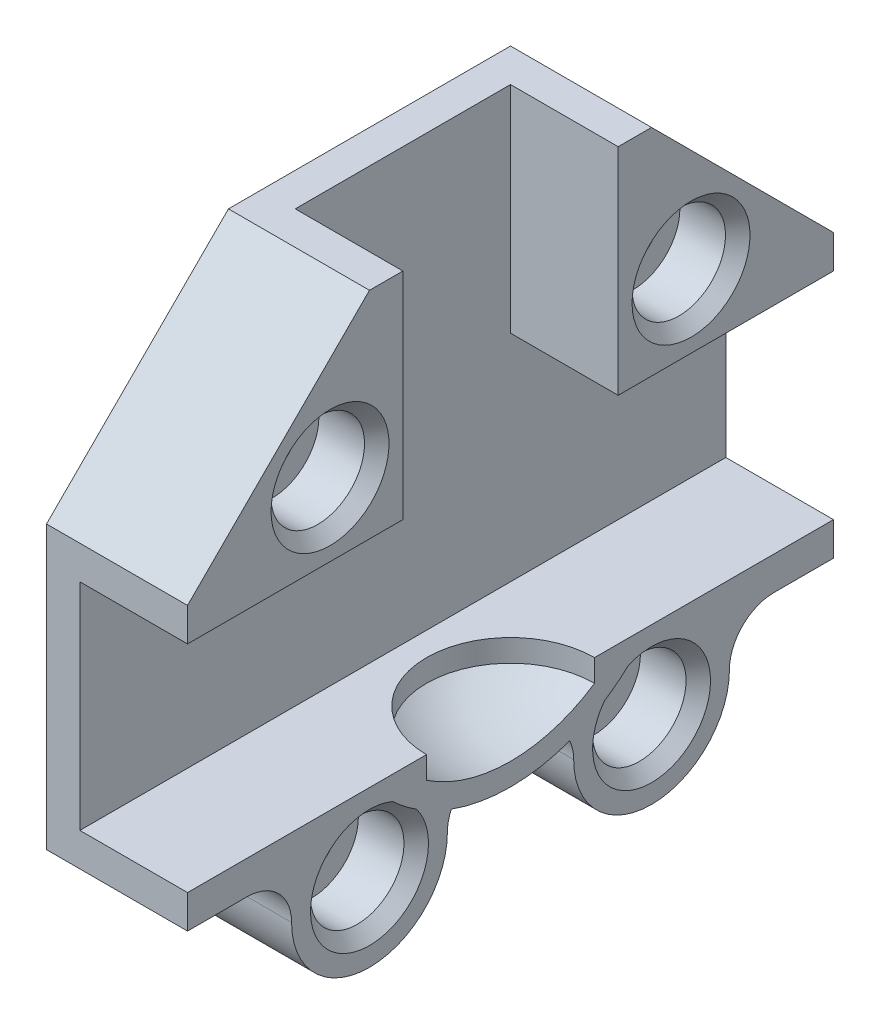
SolidWorks part; units mm, degrees
ref_plane "Front Plane" through (0, 0, 0) normal (0, 0, 1) x (1, 0, 0)
ref_plane "Top Plane" through (0, 0, 0) normal (0, 1, 0) x (1, 0, 0)
ref_plane "Right Plane" through (0, 0, 0) normal (1, 0, 0) x (0, 0, -1)
sketch "Sketch1" plane through (0, 0, 0) normal (1, 0, 0) x (0, 0, -1)
  line L0 (-29.025, 0) -> (29.025, 0) construction
  line L1 (0, 0) -> (0, 29.025) construction
  line L2 (-29.025, -9.675) -> (29.025, -9.675)
  line L3 (-9.675, 29.025) -> (-9.675, 9.675)
  line L4 (-9.675, 9.675) -> (-29.025, 9.675)
  line L5 (9.675, 29.025) -> (9.675, 9.675)
  line L6 (9.675, 9.675) -> (29.025, 9.675)
  line L7 (-9.675, 29.025) -> (9.675, 29.025) construction
  line L8 (-29.025, 9.675) -> (-29.025, -9.675) construction
  line L9 (29.025, 9.675) -> (29.025, -9.675) construction
  point P2 (0, 0)
  point P13 (0, 29.025)
  point P15 (-29.025, 0)
  point P17 (29.025, 0)
  dimension "D1" = 19.35
sketch "Sketch2" plane through (0, 0, 0) normal (1, 0, 0) x (0, 0, -1)
  line L0 (9.675, 29.025) -> (9.675, 9.675) construction
  line L1 (9.675, 9.675) -> (29.025, 9.675) construction
  line L2 (-9.675, 29.025) -> (-9.675, 9.675) construction
  line L3 (-9.675, 9.675) -> (-29.025, 9.675) construction
  line L4 (-29.025, -9.675) -> (29.025, -9.675) construction
  line L5 (9.675, 29.025) -> (9.675, 9.675) construction
  line L6 (9.675, 9.675) -> (29.025, 9.675) construction
  line L7 (-9.675, 29.025) -> (-9.675, 9.675) construction
  line L8 (-9.675, 9.675) -> (-29.025, 9.675) construction
  line L9 (-29.025, -9.675) -> (29.025, -9.675) construction
  line L10 (-12.675, 29.025) -> (-12.675, 12.675) construction
  line L11 (-12.675, 12.675) -> (-29.025, 12.675) construction
  line L12 (12.675, 29.025) -> (12.675, 12.675) construction
  line L13 (12.675, 12.675) -> (29.025, 12.675) construction
  line L14 (-29.025, -12.675) -> (29.025, -12.675) construction
  line L15 (-29.025, 9.675) -> (-29.025, 12.675)
  line L16 (-29.025, 12.675) -> (-12.675, 29.025)
  line L17 (-12.675, 29.025) -> (-9.675, 29.025)
  line L18 (-9.675, 29.025) -> (-9.675, 9.675)
  line L19 (-9.675, 9.675) -> (-29.025, 9.675)
  line L20 (-29.025, -9.675) -> (-29.025, -12.675)
  line L21 (-29.025, -12.675) -> (29.025, -12.675)
  line L22 (29.025, -12.675) -> (29.025, -9.675)
  line L23 (29.025, -9.675) -> (-29.025, -9.675)
  line L24 (9.675, 29.025) -> (12.675, 29.025)
  line L25 (12.675, 29.025) -> (29.025, 12.675)
  line L26 (29.025, 12.675) -> (29.025, 9.675)
  line L27 (29.025, 9.675) -> (9.675, 9.675)
  line L28 (9.675, 9.675) -> (9.675, 29.025)
  dimension "D1" = 3
  dimension "D2" = 3
  dimension "D3" = 3
extrude "Boss-Extrude1" add sketch "Sketch2" against normal blind 9.675
sketch "Sketch3" plane through (-9.675, 0, 0) normal (-1, 0, 0) x (0, 0, 1)
  line L0 (-29.025, 12.675) -> (-12.675, 29.025)
  line L1 (-12.675, 29.025) -> (12.675, 29.025)
  line L2 (12.675, 29.025) -> (29.025, 12.675)
  line L3 (29.025, 12.675) -> (29.025, -12.675)
  line L4 (29.025, -12.675) -> (-29.025, -12.675)
  line L5 (-29.025, -12.675) -> (-29.025, 12.675)
extrude "Boss-Extrude2" add sketch "Sketch3" along normal blind 3
sketch "Sketch4" plane through (0, 0, 0) normal (1, 0, 0) x (0, 0, -1)
  line L0 (-12.675, -16.675) -> (12.675, -16.675) construction
  line L1 (12.675, -16.675) -> (29.025, -16.675) construction
  line L2 (-12.675, -16.675) -> (-29.025, -16.675) construction
  line L3 (-29.025, -9.675) -> (-29.025, 9.675) construction
  line L4 (29.025, 9.675) -> (29.025, -9.675) construction
  line L7 (29.025, -9.675) -> (-29.025, -9.675) construction
  circle A0 centre (-12.675, -16.675) radius 5
  circle A1 centre (12.675, -16.675) radius 5
  circle A2 centre (-12.675, -16.675) radius 7
  circle A3 centre (12.675, -16.675) radius 7
  dimension "D1" = 10
  dimension "D2" = 2
sketch "Sketch5" plane through (0, 0, 0) normal (1, 0, 0) x (0, 0, -1)
  line L0 (-12.675, -16.675) -> (-29.025, -16.675) construction
  line L1 (12.675, -16.675) -> (29.025, -16.675) construction
  line L2 (-29.025, -12.675) -> (29.025, -12.675) construction
  line L3 (-29.025, -12.675) -> (-23.675, -12.675)
  line L4 (29.025, -9.675) -> (-29.025, -9.675) construction
  line L5 (29.025, -9.675) -> (-29.025, -9.675)
  line L6 (-29.025, -9.675) -> (-29.025, -12.675)
  line L7 (29.025, -9.675) -> (29.025, -12.675)
  line L8 (-1.675, -12.675) -> (1.675, -12.675)
  line L9 (23.675, -12.675) -> (29.025, -12.675)
  circle A0 centre (12.675, -16.675) radius 7 construction
  circle A1 centre (-12.675, -16.675) radius 7 construction
  arc A2 (5.675, -16.675) -> (19.675, -16.675) centre (12.675, -16.675) ccw
  arc A3 (-19.675, -16.675) -> (-5.675, -16.675) centre (-12.675, -16.675) ccw
  arc A4 (-19.675, -16.675) -> (-23.675, -12.675) centre (-23.675, -16.675) ccw
  arc A5 (23.675, -12.675) -> (19.675, -16.675) centre (23.675, -16.675) ccw
  arc A6 (-1.675, -12.675) -> (-5.675, -16.675) centre (-1.675, -16.675) ccw
  arc A7 (5.675, -16.675) -> (1.675, -12.675) centre (1.675, -16.675) ccw
extrude "Boss-Extrude3" add sketch "Sketch5" against normal up to surface (12.675 mm away) up to face at (-12.675, 9.675, 0)
sketch "Sketch6" plane through (0, 0, 0) normal (1, 0, 0) x (0, 0, -1)
  line L0 (-16.2212, 16.2212) -> (-20.85, 20.85) construction
  line L2 (-12.675, 29.025) -> (-29.025, 12.675) construction
  line L4 (-16.2212, 16.2212) -> (-9.675, 16.2212) construction
  line L6 (-9.675, 9.675) -> (-9.675, 29.025) construction
  line L8 (-16.2212, 16.2212) -> (-16.2212, 9.675) construction
  line L9 (-29.025, 9.675) -> (-9.675, 9.675) construction
  line L10 (0, 0) -> (0, 29.025) construction
  line L11 (-9.675, 29.025) -> (9.675, 29.025) construction
  circle A0 centre (-12.675, -16.675) radius 2.1
  circle A1 centre (12.675, -16.675) radius 2.1
  circle A3 centre (-16.2212, 16.2212) radius 5 construction
  circle A4 centre (-16.2212, 16.2212) radius 2.1
  circle A5 centre (16.2212, 16.2212) radius 2.1
  dimension "D1" = 10
  dimension "D2" = 4.2
extrude "Cut-Extrude1" cut sketch "Sketch6" against normal through all
sketch "Sketch7" plane through (-12.675, 0, 0) normal (-1, 0, 0) x (0, 0, 1)
  circle A0 centre (-16.2212, 16.2212) radius 5
  circle A1 centre (16.2212, 16.2212) radius 5
  circle A2 centre (-12.675, -16.675) radius 5
  circle A3 centre (12.675, -16.675) radius 5
  dimension "D1" = 10
extrude "Cut-Extrude2" cut sketch "Sketch7" against normal blind 1.5
sketch "Sketch8" plane through (0, 0, 0) normal (1, 0, 0) x (0, 0, -1)
  circle A0 centre (-16.2212, 16.2212) radius 4.2
  circle A1 centre (16.2212, 16.2212) radius 4.2
  circle A2 centre (12.675, -16.675) radius 4.2
  circle A3 centre (-12.675, -16.675) radius 4.2
  arc A5 (-19.675, -16.675) -> (-5.675, -16.675) centre (-12.675, -16.675) ccw construction
  dimension "D1" = 2.8
extrude "Cut-Extrude3" cut sketch "Sketch8" against normal blind 5.2
chamfer "Chamfer1" distance 1.1 angle 45 4 edges at (0, -16.675, -16.875) (0, -16.675, 8.475) (0, 16.2212, -20.4212) (0, 16.2212, 12.0212)
sketch "Sketch9" plane through (0, -9.675, 0) normal (0, 1, 0) x (1, 0, 0)
  circle A0 centre (0, 0) radius 7.55
extrude "Cut-Extrude4" cut sketch "Sketch9" against normal blind 2
sketch "Sketch10" plane through (0, 0, 0) normal (1, 0, 0) x (0, 0, -1)
  line L2 (0, -15.975) -> (0, -11.675)
  line L3 (0, -11.675) -> (-10.7317, -11.675)
  line L4 (0, -15.975) -> (0, -11.675)
  line L5 (0, -11.675) -> (-10.7317, -11.675)
  arc A1 (-10.7317, -11.675) -> (0, -15.975) centre (0, -0.4332) ccw
  arc A2 (-10.7317, -11.675) -> (0, -15.975) centre (0, -0.4332) ccw
  dimension "D1" = 0
revolve "Revolve1" add sketch "Sketch10" angle 180 about L4
sketch "Sketch11" plane through (0, 0, 0) normal (1, 0, 0) x (0, 0, -1)
  line L2 (0, -13.975) -> (0, -11.675)
  line L3 (0, -11.675) -> (-7.55, -11.675)
  line L4 (0, -13.975) -> (0, -11.675)
  line L5 (0, -11.675) -> (-7.55, -11.675)
  arc A1 (-7.55, -11.675) -> (0, -13.975) centre (0, -0.4332) ccw
  arc A2 (-7.55, -11.675) -> (0, -13.975) centre (0, -0.4332) ccw
  dimension "D1" = 0
revolve "Cut-Revolve1" cut sketch "Sketch11" angle 360 about L4
